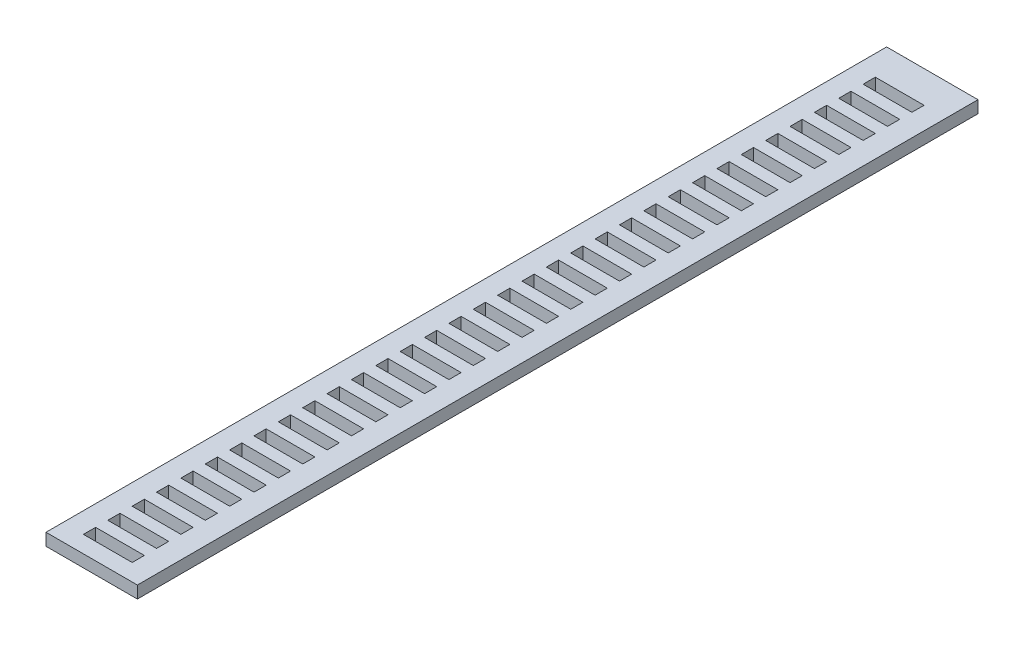
SolidWorks part; units mm, degrees
ref_plane "Front Plane" through (0, 0, 0) normal (0, 0, 1) x (1, 0, 0)
ref_plane "Top Plane" through (0, 0, 0) normal (0, 1, 0) x (1, 0, 0)
ref_plane "Right Plane" through (0, 0, 0) normal (1, 0, 0) x (0, 0, -1)
sketch "Sketch1" plane through (0, 0, 0) normal (0, 1, 0) x (1, 0, 0)
  line L1 (0, 0) -> (-15, 0)
  line L2 (0, 0) -> (0, -138)
  line L3 (0, -138) -> (-15, -138)
  line L4 (-15, 0) -> (-15, -138)
  dimension "D1" = 138
  dimension "D2" = 15
extrude "Boss-Extrude1" add sketch "Sketch1" along normal blind 2
sketch "Sketch2" plane through (0, 2, 0) normal (0, 1, 0) x (1, 0, 0)
  line L0 (-15, -5.2252) -> (0, -5.2252)
  line L1 (-15, 0) -> (-15, -138) construction
  line L2 (0, -138) -> (0, 0) construction
  line L3 (-11.6292, 0) -> (-11.6292, -11.3004)
  line L4 (0, 0) -> (-15, 0) construction
  line L8 (-11.6292, -7.2252) -> (-3.6292, -7.2252)
  line L9 (-3.6292, -5.2252) -> (-3.6292, -7.2252)
  dimension "D1" = 8
  dimension "D2" = 2
extrude "Cut-Extrude1" cut sketch "Sketch2" against normal through all contours L9 L0 L3 L8
pattern_linear "LPattern1" count 33 spacing 4 along (0, 0, 1) of "Cut-Extrude1"
